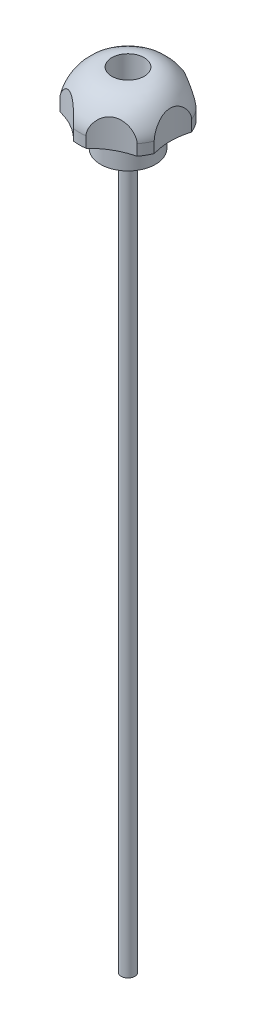
SolidWorks part; units mm, degrees
ref_plane "Alzado" through (0, 0, 0) normal (0, 0, 1) x (1, 0, 0)
ref_plane "Planta" through (0, 0, 0) normal (0, 1, 0) x (1, 0, 0)
ref_plane "Vista lateral" through (0, 0, 0) normal (1, 0, 0) x (0, 0, -1)
sketch "Croquis2" plane through (0, 0, 0) normal (0, 0, 1) x (1, 0, 0)
  line L0 (3.175, 330) -> (12.7, 330)
  line L2 (0, 0) -> (0, 350)
  line L3 (12.7, 330) -> (12.7, 347.7)
  line L4 (3.175, 0) -> (3.175, 330)
  line L5 (7.5, 350) -> (0, 350)
  line L6 (13.4838, 347.7) -> (-49986.5162, 347.7) construction
  line L8 (18.5027, 342.7) -> (22.5, 342.7)
  line L9 (22.5, 342.7) -> (22.5, 347.7)
  line L10 (0, 150) -> (0, 50150) construction
  line L11 (-3.9035, 362.7) -> (49996.0965, 362.7) construction
  line L12 (18.5027, 104.297) -> (18.5027, 50104.297) construction
  line L13 (7.5, 362.7) -> (7.5, 350)
  line L16 (3.175, 0) -> (0, 0)
  spline S0 degree 2 poles (12.7, 347.7) (18.5027, 347.7) (18.5027, 342.7) knots 0 0 0 1 1 1
  spline S1 degree 3 poles (7.5, 362.7) (13.7894, 362.7) (19.7675, 357.4724) (22.5, 349.7389) (22.5, 347.7) knots 0 0 0 0 0.720045 1 1 1 1
  point P8 (16.2951, 208.9767)
  point P11 (20.7157, 203.8726)
  point P18 (0, 300)
  dimension "D5" = 3.9973
  dimension "D4" = 20
  dimension "D2" = 3.175
  dimension "D3" = 20
  dimension "D6" = 22.5
  dimension "D7" = 7.5
  dimension "D8" = 12.7
  dimension "D9" = 15
  dimension "D10" = 12.7
  dimension "D11" = 15
  dimension "D12" = 9.0581
  dimension "D13" = 13.2157
  dimension "D14" = 3.3689
  dimension "D15" = 8.8274
  dimension "D16" = 350
revolve "Revolución1" add sketch "Croquis2" angle 360 about L2
sketch "Croquis3" plane through (0, 342.7, 0) normal (0, -1, 0) x (1, 0, 0)
  arc A0 (20.7727, 8.6454) -> (20.7727, -8.6454) centre (49.5, 0) ccw
  circle A1 centre (0, 0) radius 22.5 construction
  arc A2 (20.7727, 8.6454) -> (20.7727, -8.6454) centre (0, 0) cw
  arc A3 (17.8735, -13.667) -> (2.8992, -22.3124) centre (24.75, -42.8683) ccw
  arc A4 (17.8735, -13.667) -> (2.8992, -22.3124) centre (0, 0) cw
  arc A5 (-2.8992, -22.3124) -> (-17.8735, -13.667) centre (-24.75, -42.8683) ccw
  arc A6 (-2.8992, -22.3124) -> (-17.8735, -13.667) centre (0, 0) cw
  arc A7 (-20.7727, -8.6454) -> (-20.7727, 8.6454) centre (-49.5, 0) ccw
  arc A8 (-20.7727, -8.6454) -> (-20.7727, 8.6454) centre (0, 0) cw
  arc A9 (-17.8735, 13.667) -> (-2.8992, 22.3124) centre (-24.75, 42.8683) ccw
  arc A10 (-17.8735, 13.667) -> (-2.8992, 22.3124) centre (0, 0) cw
  arc A11 (2.8992, 22.3124) -> (17.8735, 13.667) centre (24.75, 42.8683) ccw
  arc A12 (2.8992, 22.3124) -> (17.8735, 13.667) centre (0, 0) cw
  point P5 (19.5, 0)
  point P10 (22.5, 0)
  point P15 (11.25, -19.4856)
  point P19 (-11.25, -19.4856)
  point P23 (-22.5, 0)
  point P27 (-11.25, 19.4856)
  point P31 (11.25, 19.4856)
  point P32 (0, 0)
  dimension "D1" = 30
  dimension "D3" = 6
  dimension "D2" = 3
extrude "Cortar-Extruir1" cut sketch "Croquis3" against normal through all
